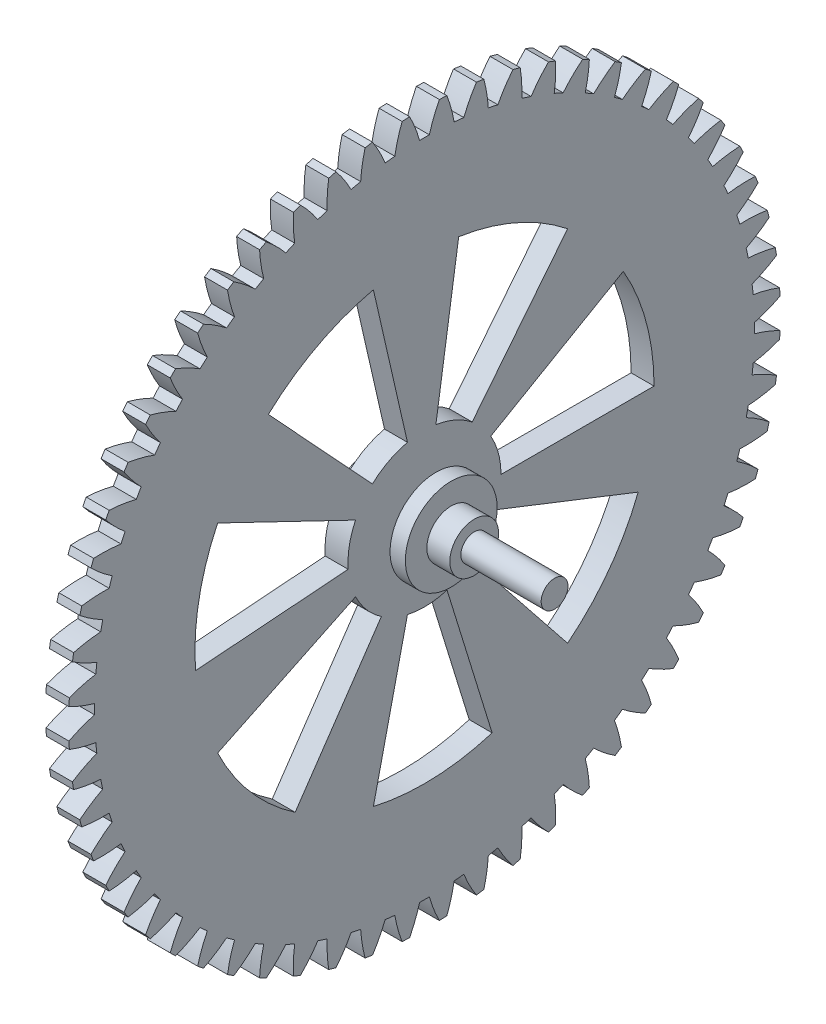
SolidWorks part; units mm, degrees
ref_plane "Plane1" through (0, 0, 0) normal (0, 0, 1) x (1, 0, 0)
ref_plane "Plane2" through (0, 0, 0) normal (0, 1, 0) x (1, 0, 0)
ref_plane "Plane3" through (0, 0, 0) normal (1, 0, 0) x (0, 0, -1)
sketch "HoldingSke" plane through (0, 0, 0) normal (0, 1, 0) x (1, 0, 0)
  line L0 (0, 0) -> (0.3333, -0.5774)
  line L1 (-15, 0) -> (100, 0) construction
  line L2 (0, 0) -> (-2.1039, 2.3779)
  line L3 (0, 0) -> (-11.863, 4.5341)
  line L4 (0, 0) -> (4.318, 7.479)
  line L5 (0, 0) -> (-46.8476, -17.4728)
  line L6 (0, 0) -> (-2.4869, -1.6779)
  line L7 (-2.1039, 2.3779) -> (8.6586, 51.2059)
  line L8 (-76.2, 54.61) -> (-76.1, 54.61)
  line L9 (-71.009, 38.7566) -> (-53.1078, 45.2721)
  line L10 (-76.2, 71.12) -> (104.1128, 71.12)
  line L11 (0, 0) -> (-3, 0)
  line L12 (-76.2, 101.6) -> (-76.147, 101.6)
  line L13 (24.9733, 27.94) -> (52.9518, 28.4284)
  line L14 (24.9733, 27.94) -> (24.9743, 27.94)
  line L15 (24.9733, 27.94) -> (100.4006, 29.5858)
  line L16 (-63.627, -1.5) -> (-12.827, -1.5)
  circle A0 centre (0, 0) radius 0.5
  circle A1 centre (0, 0) radius 37.5
  circle A2 centre (0, 0) radius 37.5
  circle A3 centre (0, 0) radius 0.5
  dimension "MHD" = 75
  dimension "Hub_dia" = 75
  dimension "Bore" = 1
  dimension "MBD" = 1
  dimension "Num_teeth" = 60
  dimension "Pitch" = 0.6667
  dimension "Overall_len" = 50
  dimension "Show_teeth" = 60
  dimension "Thickness" = 3
  dimension "OAL" = 50.0001
  dimension "T_dim" = 0.1
  dimension "Ap" = 20
  dimension "H" = 19.05
  dimension "Pitch_radius" = 180.3128
  dimension "Width" = 3
  dimension "Backlash" = 0.053
  dimension "Addendum_fac" = 1
  dimension "Dedendum_fac" = 1.25
  dimension "Clearance_fac" = 0.25
  dimension "Dedendum_add" = 0.001
  dimension "Module" = 1.5
sketch "BasProSke" plane through (0, 0, 0) normal (0, 1, 0) x (1, 0, 0)
  line L0 (-10, 0) -> (60, 0) construction
  line L1 (0, 0) -> (0, 46.5)
  line L2 (0, 0) -> (3, 0)
  line L3 (3, 0) -> (3, 46.5)
  line L4 (3, 46.5) -> (0, 46.5)
  dimension "Thickness" = 3
  dimension "Diameter" = 93
revolve "Base-Revolve" add sketch "BasProSke" angle 360 about L0
sketch "TooCutSke" plane through (0, 0, 0) normal (1, 0, 0) x (0, 0, -1)
  line L1 (0, 0) -> (0, 107) construction
  line L2 (0, 0) -> (-1.2707, 44.9821) construction
  line L3 (0, 0) -> (-4.7089, 89.8505) construction
  line L4 (-1.2707, 44.9821) -> (-2.3544, 44.9253) construction
  arc A0 (0.6387, 43.1193) -> (-0.6387, 43.1193) centre (0, 0) ccw
  arc A1 (1.9554, 46.4843) -> (-1.9554, 46.4843) centre (0, 0) ccw
  circle A2 centre (0, 0) radius 45 construction
  circle A3 centre (0, 0) radius 42.2862 construction
  arc A4 (-0.6387, 43.1193) -> (-1.9554, 46.4843) centre (-17.9747, 38.2757) ccw
  arc A5 (1.9554, 46.4843) -> (0.6387, 43.1193) centre (17.9747, 38.2757) ccw
  dimension "Root_dia" = 86.248
  dimension "Overcut_dia" = 93.0508
  dimension "Pitch_dia" = 90
  dimension "Base_dia" = 84.5723
  dimension "Flank_rad" = 18
  dimension "Half_ang" = 3
  dimension "Half_CT" = 1.0852
extrude "ToothCut" cut sketch "TooCutSke" along normal through all
fillet "Breaks" [suppressed] radius 0.03
fillet "RootFillets" [suppressed] radius 0.376
pattern_circular "TeethCuts" count 60 every 6 about axis through (-10, 0, 0) along (1, 0, 0) of "ToothCut", "RootFillets", "Breaks"
sketch "HubNeaOneSke" plane through (0, 0, 0) normal (-1, 0, 0) x (0, 0, 1)
  circle A0 centre (0, 0) radius 37.5
  dimension "Diameter" = 75
extrude "HubNearOne" [suppressed] add sketch "HubNeaOneSke" along normal blind 47.0001
sketch "HubNeaBotSke" plane through (0, 0, 0) normal (-1, 0, 0) x (0, 0, 1)
  circle A0 centre (0, 0) radius 37.5
  dimension "Diameter" = 75
extrude "HubNearBoth" [suppressed] add sketch "HubNeaBotSke" along normal blind 23.5
ref_plane "FarPln" through (3, 0, 0) normal (1, 0, 0) x (0, 0, -1)
sketch "HubFarSke" plane through (3, 0, 0) normal (1, 0, 0) x (0, 0, -1)
  circle A0 centre (0, 0) radius 37.5
  dimension "Diameter" = 75
extrude "HubFar" [suppressed] add sketch "HubFarSke" along normal blind 23.5
sketch "BorSke" plane through (0, 0, 0) normal (1, 0, 0) x (0, 0, -1)
  circle A0 centre (0, 0) radius 0.5
  dimension "Diameter" = 1
extrude "Bore" cut sketch "BorSke" along normal mid plane 100.0001
sketch "KeySke" plane through (0, 0, 0) normal (1, 0, 0) x (0, 0, -1)
  line L0 (-0.05, 0) -> (-0.05, 0.6)
  line L1 (-0.05, 0.6) -> (0.05, 0.6)
  line L2 (0.05, 0.6) -> (0.05, 0)
  line L3 (0, 0) -> (0, 34) construction
  line L4 (-0.05, 0) -> (0.05, 0)
  dimension "Offset" = 0.6
  dimension "Width" = 0.1
extrude "Keyway" [suppressed] cut sketch "KeySke" along normal mid plane 100.0001
pattern_circular "Keyway2" [suppressed] count 2 every 90 about axis through (-10, 0, 0) along (1, 0, 0)
sketch "Sketch1" plane through (3, 0, 0) normal (1, 0, 0) x (0, 0, -1)
  text T0 "FRONT"
sketch "Sketch2" plane through (0, 0, 0) normal (-1, 0, 0) x (0, 0, 1)
  circle A0 centre (0, 0) radius 3.1875
  dimension "D1" = 6.375
extrude "Boss-Extrude1" add sketch "Sketch2" along normal blind 5 and the other way blind 20
sketch "Sketch6" plane through (3, 0, 0) normal (1, 0, 0) x (0, 0, -1)
  circle A0 centre (0, 0) radius 30.7209 construction
sketch "Sketch7" plane through (3, 0, 0) normal (1, 0, 0) x (0, 0, -1)
  circle A0 centre (0, 0) radius 6
extrude "Boss-Extrude5" add sketch "Sketch7" along normal blind 2 from offset 1.5
sketch "Sketch8" plane through (3, 0, 0) normal (1, 0, 0) x (0, 0, -1)
  line L0 (0, 0) -> (0, 50.5234) construction
  line L1 (0, 0) -> (82.2995, 0) construction
  line L2 (0, 0) -> (68.5072, 39.5526) construction
  line L3 (25.9808, 15) -> (8.6603, 5)
  line L4 (10, 0) -> (30, 0)
  line L5 (6.2349, -7.8183) -> (18.7047, -23.4549)
  line L6 (27.9262, -10.9602) -> (9.3087, -3.6534)
  line L7 (-2.2252, -9.7493) -> (-6.6756, -29.2478)
  line L8 (8.8427, -28.6672) -> (2.9476, -9.5557)
  line L9 (-9.0097, -4.3388) -> (-27.0291, -13.0165)
  line L10 (-16.8996, -24.7872) -> (-5.6332, -8.2624)
  line L11 (-9.0097, 4.3388) -> (-27.0291, 13.0165)
  line L12 (-29.9161, -2.2419) -> (-9.972, -0.7473)
  line L13 (-2.2252, 9.7493) -> (-6.6756, 29.2478)
  line L14 (-20.4052, 21.9916) -> (-6.8017, 7.3305)
  line L15 (6.2349, 7.8183) -> (18.7047, 23.4549)
  line L16 (4.4713, 29.6649) -> (1.4904, 9.8883)
  circle A0 centre (0, 0) radius 30.7209 construction
  arc A1 (10, 0) -> (8.6603, 5) centre (0, 0) ccw
  arc A2 (30, 0) -> (25.9808, 15) centre (0, 0) ccw
  arc A3 (18.7047, -23.4549) -> (27.9262, -10.9602) centre (0, 0) ccw
  arc A4 (6.2349, -7.8183) -> (9.3087, -3.6534) centre (0, 0) ccw
  arc A5 (-6.6756, -29.2478) -> (8.8427, -28.6672) centre (0, 0) ccw
  arc A6 (-2.2252, -9.7493) -> (2.9476, -9.5557) centre (0, 0) ccw
  arc A7 (-27.0291, -13.0165) -> (-16.8996, -24.7872) centre (0, 0) ccw
  arc A8 (-9.0097, -4.3388) -> (-5.6332, -8.2624) centre (0, 0) ccw
  arc A9 (-27.0291, 13.0165) -> (-29.9161, -2.2419) centre (0, 0) ccw
  arc A10 (-9.0097, 4.3388) -> (-9.972, -0.7473) centre (0, 0) ccw
  arc A11 (-6.6756, 29.2478) -> (-20.4052, 21.9916) centre (0, 0) ccw
  arc A12 (-2.2252, 9.7493) -> (-6.8017, 7.3305) centre (0, 0) ccw
  arc A13 (18.7047, 23.4549) -> (4.4713, 29.6649) centre (0, 0) ccw
  arc A14 (6.2349, 7.8183) -> (1.4904, 9.8883) centre (0, 0) ccw
  point P3 (8.6603, 5)
  point P6 (26.6051, 15.3604)
  point P13 (9.6593, 2.5882)
  point P36 (0, 0)
  dimension "D4" = 30
  dimension "D1" = 30
  dimension "D3" = 10
  dimension "D2" = 7
extrude "Cut-Extrude1" cut sketch "Sketch8" against normal up to next contours A10 L11 A9 L12 | A8 L9 A7 L10 | A6 L7 A5 L8 | A4 L5 A3 L6 | A12 L13 A11 L14 | L4 A2 L3 A1 | L15 A13 L16 A14
sketch "Sketch4" plane through (3, 0, 0) normal (1, 0, 0) x (0, 0, -1)
  circle A0 centre (0, 0) radius 0.5
sketch "Sketch5" plane through (3, 0, 0) normal (1, 0, 0) x (0, 0, -1)
  circle A0 centre (0, 0) radius 1
ref_plane "Plane4" through (9.5, 0, 0) normal (1, 0, 0) x (0, 0, -1)
sketch "Sketch9" plane through (20, 0, 0) normal (1, 0, 0) x (0, 0, -1)
  circle A0 centre (0, 0) radius 1.75
  circle A1 centre (0, 0) radius 3.1875
  circle A2 centre (0, 0) radius 3.1875
  dimension "D2" = 3.5
  dimension "D1" = 0
extrude "Cut-Extrude2" cut sketch "Sketch9" along normal up to next from surface
equation "' \"Module@HoldingSke\" = 6.35"
equation "' \"Num_teeth@HoldingSke\" = 12"
equation "' \"Ap@HoldingSke\" =  20"
equation "' \"Ap@HoldingSke\" = 20"
equation "' \"Width@HoldingSke\" = 0.5 * 25.4"
equation "' \"Hub_dia@HoldingSke\"= 1 * 25.4"
equation "' \"Hub_dia@HoldingSke\" = 1 * 25.4"
equation "' \"Overall_len@HoldingSke\" = 1.0 * 25.4"
equation "' \"Bore@HoldingSke\" = 0.75 * 25.4"
equation "' \"T_dim@HoldingSke\" = 0.1 * 25.4"
equation "' \"Width@KeySke\" = 0.25 * 25.4"
equation "' \"Show_teeth@HoldingSke\" = 13"
equation "' \"Backlash@HoldingSke\" = 0.009 * 25.4"
equation "' \"Addendum_fac@HoldingSke\" = 1.0"
equation "' \"Dedendum_fac@HoldingSke\" = 1.25"
equation "' \"Dedendum_add@HoldingSke\" = 0.00005 * 25.4"
equation "' \"Clearance_fac@HoldingSke\" = 0.25"
equation "\"Pitch@HoldingSke\" = 1 / \"Module@HoldingSke\""
equation "\"Overcut_dia@TooCutSke\" = (\"Num_teeth@HoldingSke\" + 2 * \"Addendum_fac@HoldingSke\") / \"Pitch@HoldingSke\" + 0.002 * 25.4"
equation "\"Pitch_dia@TooCutSke\" = \"Num_teeth@HoldingSke\" / \"Pitch@HoldingSke\""
equation "\"Base_dia@TooCutSke\" = \"Num_teeth@HoldingSke\" / \"Pitch@HoldingSke\" * cos((\"Ap@HoldingSke\"  * 3.14159265 / 180))"
equation "\"Root_dia@TooCutSke\" = (\"Num_teeth@HoldingSke\" + 2) / \"Pitch@HoldingSke\" - 2 * (\"Addendum_fac@HoldingSke\" + \"Dedendum_fac@HoldingSke\") / \"Pitch@HoldingSke\" - \"Dedendum_add@HoldingSke\" * 2"
equation "\"Half_ang@TooCutSke\" = 180 / \"Num_teeth@HoldingSke\""
equation "\"Half_CT@TooCutSke\" = \"Num_teeth@HoldingSke\" / \"Pitch@HoldingSke\" * sin((3.14159265 / 2 / \"Num_teeth@HoldingSke\")) / 2 - 7 * \"Backlash@HoldingSke\" / 4"
equation "\"Flank_rad@TooCutSke\" = \"Num_teeth@HoldingSke\" / \"Pitch@HoldingSke\" / 5"
equation "\"Radius@RootFillets\" = \"Clearance_fac@HoldingSke\" / \"Pitch@HoldingSke\" + \"Dedendum_add@HoldingSke\""
equation "\"Break_rad@Breaks\" = 0.02 / \"Pitch@HoldingSke\""
equation "\"Thickness@HoldingSke\" = \"Width@HoldingSke\""
equation "\"OAL@HoldingSke\" = \"Thickness@HoldingSke\""
equation "\"MHD@HoldingSke\" = (\"Num_teeth@HoldingSke\" + 2) / \"Pitch@HoldingSke\" - 2 * (\"Addendum_fac@HoldingSke\" + \"Dedendum_fac@HoldingSke\")  / \"Pitch@HoldingSke\" - \"Dedendum_add@HoldingSke\" * 2"
equation "\"MBD@HoldingSke\" = (\"Num_teeth@HoldingSke\" + 2) / \"Pitch@HoldingSke\" - 2 * (\"Addendum_fac@HoldingSke\" + \"Dedendum_fac@HoldingSke\")  / \"Pitch@HoldingSke\" - \"Dedendum_add@HoldingSke\" * 2 - 0.002 * 25.4"
equation "\"MHD@HoldingSke\" = ((sgn( \"MHD@HoldingSke\" - \"Hub_dia@HoldingSke\" )-1)*( \"MHD@HoldingSke\" - \"Hub_dia@HoldingSke\" ))/-2+ \"Hub_dia@HoldingSke\""
equation "\"MBD@HoldingSke\" = ((sgn( \"MBD@HoldingSke\" - \"Bore@HoldingSke\" )-1)*( \"MBD@HoldingSke\" - \"Bore@HoldingSke\" ))/-2+ \"Bore@HoldingSke\""
equation "\"OAL@HoldingSke\" = ((sgn( \"OAL@HoldingSke\" - \"Overall_len@HoldingSke\" )+1)*( \"OAL@HoldingSke\" - \"Overall_len@HoldingSke\" ))/2 + \"Overall_len@HoldingSke\" + 0.000002 * 25.4"
equation "\"Num_teeth@TeethCuts\" = int( \"Show_teeth@HoldingSke\" ) + 1"
equation "\"Num_teeth@TeethCuts\" = ((sgn( \"Num_teeth@TeethCuts\" - \"Num_teeth@HoldingSke\" )-1)*( \"Num_teeth@TeethCuts\" - \"Num_teeth@HoldingSke\" ))/-2+ \"Num_teeth@HoldingSke\""
equation "\"Num_teeth@TeethCuts\" = ((sgn( \"Num_teeth@TeethCuts\" - 2.0)+1)*( \"Num_teeth@TeethCuts\" - 2.0))/2 +2.0"
equation "\"Angle@TeethCuts\" = 360.0 / \"Num_teeth@HoldingSke\""
equation "\"Diameter@BasProSke\" = (\"Num_teeth@HoldingSke\" + 2 * \"Addendum_fac@HoldingSke\") / \"Pitch@HoldingSke\""
equation "\"Thickness@BasProSke\"  = \"Thickness@HoldingSke\""
equation "' \"Fillet_rad@BasProSke\" =  \"Thickness@HoldingSke\" * 0.05"
equation "' \"Fillet_rad@BasProSke\" = \"Thickness@HoldingSke\" * 0.05"
equation "\"MHD@HoldingSke\" = ((sgn( \"MHD@HoldingSke\" - \"Root_dia@TooCutSke\" )-1)*( \"MHD@HoldingSke\" - \"Root_dia@TooCutSke\" ))/-2+ \"Root_dia@TooCutSke\""
equation "\"Diameter@HubNeaOneSke\" = \"MHD@HoldingSke\""
equation "\"Length@HubNearOne\" = \"OAL@HoldingSke\" - \"Thickness@BasProSke\""
equation "\"Diameter@HubNeaBotSke\" = \"MHD@HoldingSke\""
equation "\"Length@HubNearBoth\" = ( \"OAL@HoldingSke\" - \"Thickness@BasProSke\" ) / 2.0"
equation "\"Thickness@FarPln\" = \"Thickness@BasProSke\""
equation "\"Diameter@HubFarSke\" = \"MHD@HoldingSke\""
equation "\"Length@HubFar\" = ( \"OAL@HoldingSke\" - \"Thickness@BasProSke\" ) / 2.0"
equation "\"Diameter@BorSke\" = \"MBD@HoldingSke\""
equation "\"D1@Bore\" = \"OAL@HoldingSke\" * 2.0"
equation "\"D1@Keyway\" = \"OAL@HoldingSke\" * 2.0"
equation "\"Offset@KeySke\" = \"T_dim@HoldingSke\" + \"MBD@HoldingSke\" / 2.0"
